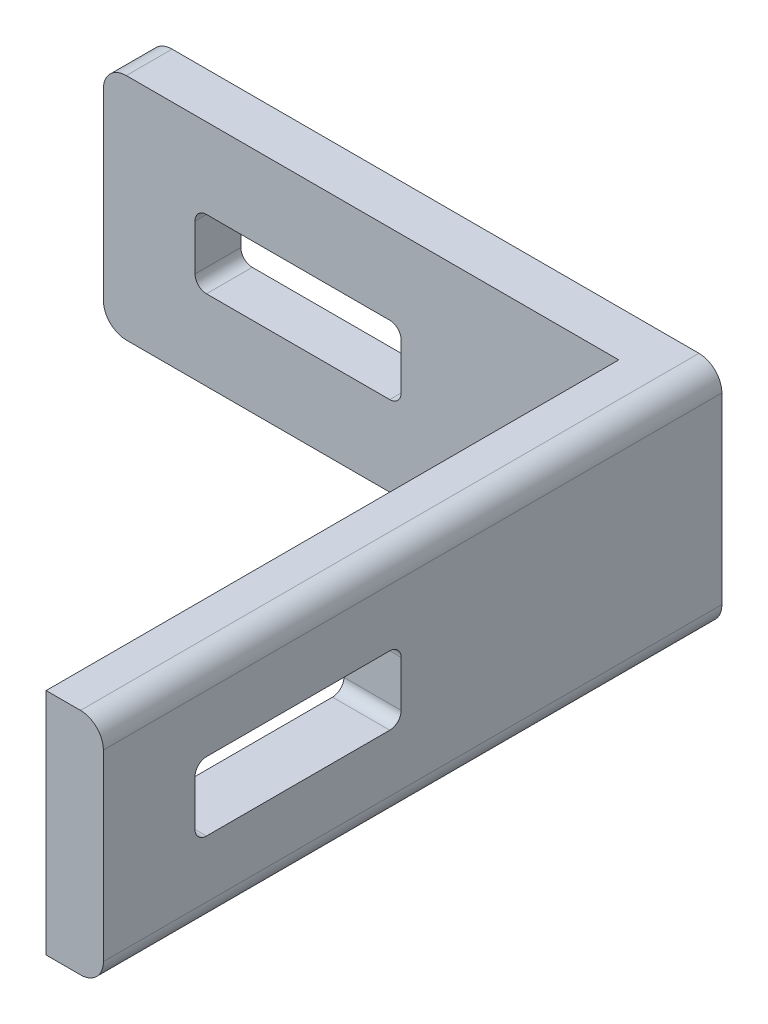
SolidWorks part; units mm, degrees
ref_plane "Plan de face" through (0, 0, 0) normal (0, 0, 1) x (1, 0, 0)
ref_plane "Plan de dessus" through (0, 0, 0) normal (0, 1, 0) x (1, 0, 0)
ref_plane "Plan de droite" through (0, 0, 0) normal (1, 0, 0) x (0, 0, -1)
sketch "Esquisse1" plane through (0, 0, 0) normal (0, 0, 1) x (1, 0, 0)
  line L1 (-11.2733, 8.7087) -> (34.7267, 8.7087)
  line L2 (-13.2733, 6.7087) -> (-13.2733, -9.2913)
  line L3 (-11.2733, -11.2913) -> (34.7267, -11.2913)
  line L4 (36.7267, 6.7087) -> (36.7267, -9.2913)
  arc A0 (34.7267, 8.7087) -> (36.7267, 6.7087) centre (34.7267, 6.7087) cw
  arc A1 (36.7267, -9.2913) -> (34.7267, -11.2913) centre (34.7267, -9.2913) cw
  arc A2 (-11.2733, -11.2913) -> (-13.2733, -9.2913) centre (-11.2733, -9.2913) cw
  arc A3 (-13.2733, 6.7087) -> (-11.2733, 8.7087) centre (-11.2733, 6.7087) cw
  point P8 (36.7267, -11.2913)
  point P11 (-13.2733, -11.2913)
  point P14 (-13.2733, 8.7087)
  dimension "D3" = 2
  dimension "D1" = 20
  dimension "D2" = 50
extrude "Boss.-Extru.1" add sketch "Esquisse1" along normal blind 4
sketch "Esquisse2" plane through (0, 0, 4) normal (0, 0, 1) x (1, 0, 0)
  line L1 (31.7267, 8.7087) -> (34.7267, 8.7087)
  line L2 (31.7267, 8.7087) -> (31.7267, -11.2913)
  line L3 (31.7267, -11.2913) -> (34.7267, -11.2913)
  line L4 (36.7267, 6.7087) -> (36.7267, -9.2913)
  line L5 (36.7267, -9.2913) -> (36.7267, 6.7087) construction
  line L6 (34.7267, 8.7087) -> (-11.2733, 8.7087) construction
  line L7 (-11.2733, -11.2913) -> (34.7267, -11.2913) construction
  arc A0 (34.7267, 8.7087) -> (36.7267, 6.7087) centre (34.7267, 6.7087) cw
  arc A1 (36.7267, -9.2913) -> (34.7267, -11.2913) centre (34.7267, -9.2913) cw
  dimension "D1" = 2
  dimension "D2" = 3
extrude "Boss.-Extru.3" add sketch "Esquisse2" along normal blind 50
sketch "Esquisse3" plane through (0, 0, 4) normal (0, 0, 1) x (1, 0, 0)
  line L0 (-13.2733, 6.7087) -> (-13.2733, -9.2913) construction
  line L1 (-4.2733, 1.7087) -> (11.7267, 1.7087)
  line L2 (-5.2733, 0.7087) -> (-5.2733, -3.2913)
  line L3 (-4.2733, -4.2913) -> (11.7267, -4.2913)
  line L4 (12.7267, 0.7087) -> (12.7267, -3.2913)
  line L5 (-5.2733, 1.7087) -> (12.7267, -4.2913) construction
  line L6 (-5.2733, -4.2913) -> (12.7267, 1.7087) construction
  line L7 (-11.2733, -11.2913) -> (31.7267, -11.2913) construction
  line L8 (31.7267, 8.7087) -> (-11.2733, 8.7087) construction
  arc A0 (-5.2733, 0.7087) -> (-4.2733, 1.7087) centre (-4.2733, 0.7087) cw
  arc A1 (-5.2733, -3.2913) -> (-4.2733, -4.2913) centre (-4.2733, -3.2913) ccw
  arc A2 (11.7267, -4.2913) -> (12.7267, -3.2913) centre (11.7267, -3.2913) ccw
  arc A3 (12.7267, 0.7087) -> (11.7267, 1.7087) centre (11.7267, 0.7087) ccw
  point P0 (3.7267, -1.2913)
  dimension "D4" = 1
  dimension "D1" = 18
  dimension "D2" = 6
  dimension "D3" = 8
  dimension "D5" = 7
  dimension "D6" = 7
extrude "Enlèv. mat.-Extru.1" cut sketch "Esquisse3" against normal blind 50
sketch "Esquisse4" plane through (31.7267, 0, 0) normal (-1, 0, 0) x (0, 0, 1)
  line L0 (29, 1.7087) -> (45, 1.7087)
  line L1 (28, 0.7087) -> (28, -3.2913)
  line L2 (29, -4.2913) -> (45, -4.2913)
  line L3 (46, 0.7087) -> (46, -3.2913)
  line L4 (54, 8.7087) -> (4, 8.7087) construction
  line L8 (54, 8.7087) -> (54, -11.2913) construction
  arc A0 (28, 0.7087) -> (29, 1.7087) centre (29, 0.7087) cw
  arc A1 (28, -3.2913) -> (29, -4.2913) centre (29, -3.2913) ccw
  arc A2 (45, -4.2913) -> (46, -3.2913) centre (45, -3.2913) ccw
  arc A3 (46, 0.7087) -> (45, 1.7087) centre (45, 0.7087) ccw
  dimension "D1" = 7
  dimension "D2" = 16
  dimension "D3" = 6
  dimension "D4" = 8
extrude "Enlèv. mat.-Extru.2" cut sketch "Esquisse4" against normal blind 50
